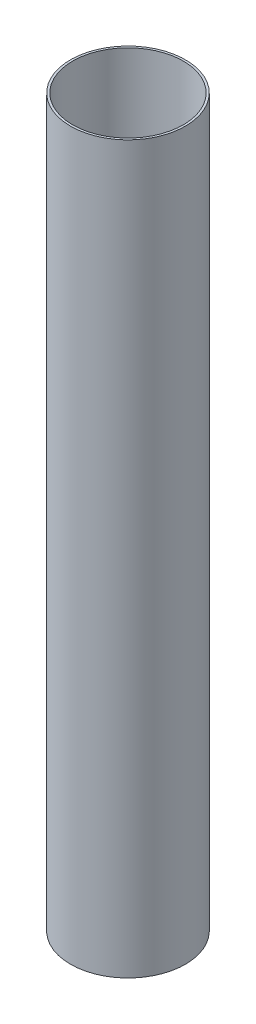
SolidWorks part; units mm, degrees
ref_plane "Front Plane" through (0, 0, 0) normal (0, 0, 1) x (1, 0, 0)
ref_plane "Top Plane" through (0, 0, 0) normal (0, 1, 0) x (1, 0, 0)
ref_plane "Right Plane" through (0, 0, 0) normal (1, 0, 0) x (0, 0, -1)
sketch "Sketch1" plane through (0, 0, 0) normal (0, 1, 0) x (1, 0, 0)
  circle A0 centre (0, 0) radius 38.1
  circle A1 centre (0, 0) radius 39.6
  dimension "D1" = 76.2
  dimension "D2" = 1.5
extrude "Boss-Extrude1" add sketch "Sketch1" along normal blind 500
sketch "Sketch2" plane through (0, 0, 0) normal (1, 0, 0) x (0, 0, -1)
  circle A0 centre (0, 310) radius 2
  dimension "D1" = 4
  dimension "D2" = 310
extrude "Cut-Extrude1" cut sketch "Sketch2" against normal up to surface (39.5495 mm away)
